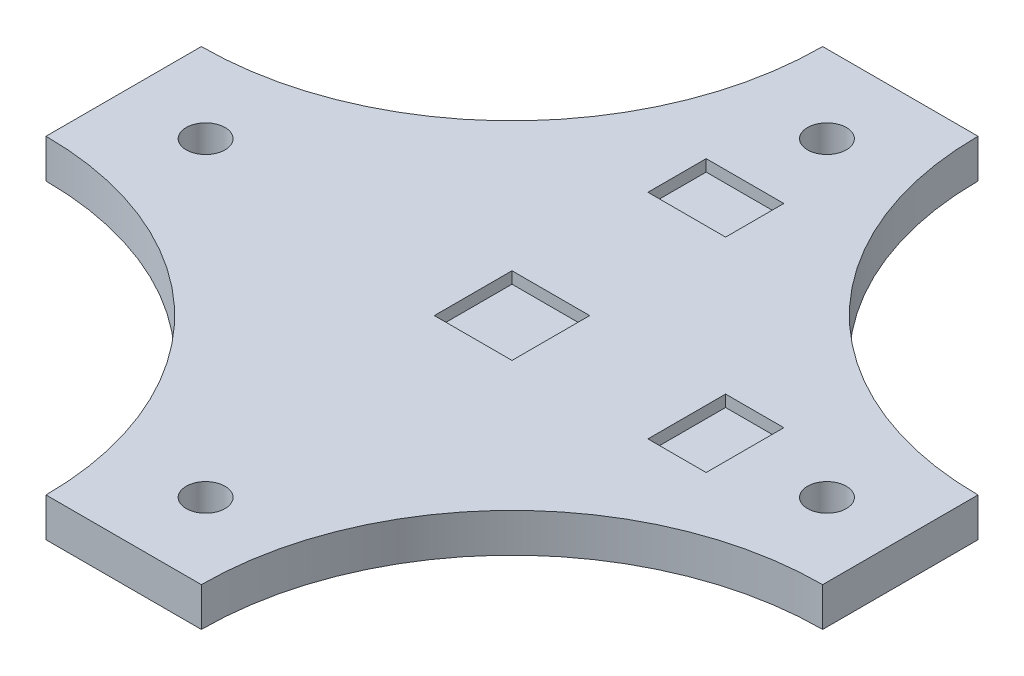
SolidWorks part; units mm, degrees
ref_plane "Alzado" through (0, 0, 0) normal (0, 0, 1) x (1, 0, 0)
ref_plane "Planta" through (0, 0, 0) normal (0, 1, 0) x (1, 0, 0)
ref_plane "Vista lateral" through (0, 0, 0) normal (1, 0, 0) x (0, 0, -1)
sketch "Croquis1" plane through (0, 0, 0) normal (0, 1, 0) x (1, 0, 0)
  line L1 (-100, 100) -> (100, 100)
  line L2 (-100, 100) -> (-100, -100)
  line L3 (-100, -100) -> (100, -100)
  line L4 (100, 100) -> (100, -100)
  line L5 (-100, 100) -> (100, -100) construction
  line L6 (-100, -100) -> (100, 100) construction
  point P0 (0, 0)
  dimension "D1" = 200
  dimension "D2" = 200
extrude "Saliente-Extruir1" add sketch "Croquis1" along normal blind 10
sketch "Croquis2" plane through (0, 10, 0) normal (0, 1, 0) x (1, 0, 0)
  line L1 (-10, 10) -> (10, 10)
  line L2 (-10, 10) -> (-10, -10)
  line L3 (-10, -10) -> (10, -10)
  line L4 (10, 10) -> (10, -10)
  line L5 (-10, 10) -> (10, -10) construction
  line L6 (-10, -10) -> (10, 10) construction
  line L7 (-10, 60) -> (10, 60)
  line L8 (-10, 60) -> (-10, 45)
  line L9 (-10, 45) -> (10, 45)
  line L10 (10, 60) -> (10, 45)
  line L11 (-10, 60) -> (10, 45) construction
  line L12 (-10, 45) -> (10, 60) construction
  line L13 (45, 10) -> (60, 10)
  line L14 (45, 10) -> (45, -10)
  line L15 (45, -10) -> (60, -10)
  line L16 (60, 10) -> (60, -10)
  line L17 (45, 10) -> (60, -10) construction
  line L18 (45, -10) -> (60, 10) construction
  line L21 (100, 100) -> (-100, 100) construction
  line L22 (100, -100) -> (100, 100) construction
  line L23 (-100, -100) -> (100, -100) construction
  point P0 (0, 0)
  point P6 (0, 52.5)
  point P11 (52.5, 0)
  dimension "D1" = 20
  dimension "D2" = 20
  dimension "D3" = 20
  dimension "D4" = 15
  dimension "D5" = 15
  dimension "D6" = 20
  dimension "D7" = 90
  dimension "D8" = 40
  dimension "D9" = 90
  dimension "D10" = 40
extrude "Cortar-Extruir1" cut sketch "Croquis2" against normal blind 3
sketch "Croquis3" plane through (0, 10, 0) normal (0, 1, 0) x (1, 0, 0)
  line L0 (-100, -100) -> (100, -100) construction
  line L1 (-20, 100) -> (20, 100)
  line L2 (-20, 100) -> (-20, -100)
  line L3 (-20, -100) -> (20, -100)
  line L4 (20, 100) -> (20, -100)
  line L5 (-20, 100) -> (20, -100) construction
  line L6 (-20, -100) -> (20, 100) construction
  line L7 (100, -100) -> (100, 100) construction
  line L8 (-100, 20) -> (100, 20)
  line L9 (-100, 20) -> (-100, -20)
  line L10 (-100, -20) -> (100, -20)
  line L11 (100, 20) -> (100, -20)
  line L12 (-100, 20) -> (100, -20) construction
  line L13 (-100, -20) -> (100, 20) construction
  arc A0 (-20, -100) -> (-100, -20) centre (-100, -100) ccw
  arc A1 (20, -100) -> (100, -20) centre (100, -100) cw
  arc A2 (20, 100) -> (100, 20) centre (100, 100) ccw
  arc A3 (-20, 100) -> (-100, 20) centre (-100, 100) cw
  point P0 (0, 0)
  point P8 (0, 0)
  line M15 (100, -100) -> (100, 100)
  line M16 (100, 100) -> (-100, 100)
  line M17 (-100, 100) -> (-100, -100)
  line M18 (-100, -100) -> (100, -100)
  dimension "D1" = 40
  dimension "D2" = 40
extrude "Cortar-Extruir2" cut sketch "Croquis3" against normal blind 10 contours A2 M16 M15 | A3 M16 M17 | A0 M18 M17 | A1 M18 M15
sketch "Croquis4" plane through (0, 10, 0) normal (0, 1, 0) x (1, 0, 0)
  circle A0 centre (-78.8974, 0) radius 5
  circle A1 centre (1.1026, 80) radius 5
  circle A2 centre (81.1026, 0) radius 5
  circle A3 centre (1.1026, -80) radius 5
  point P2 (0, 0)
  point P3 (0, 0)
  point P11 (1.1026, 0)
  dimension "D1" = 10
  dimension "D3" = 80
  dimension "D2" = 4
extrude "Cortar-Extruir3" cut sketch "Croquis4" against normal blind 10
